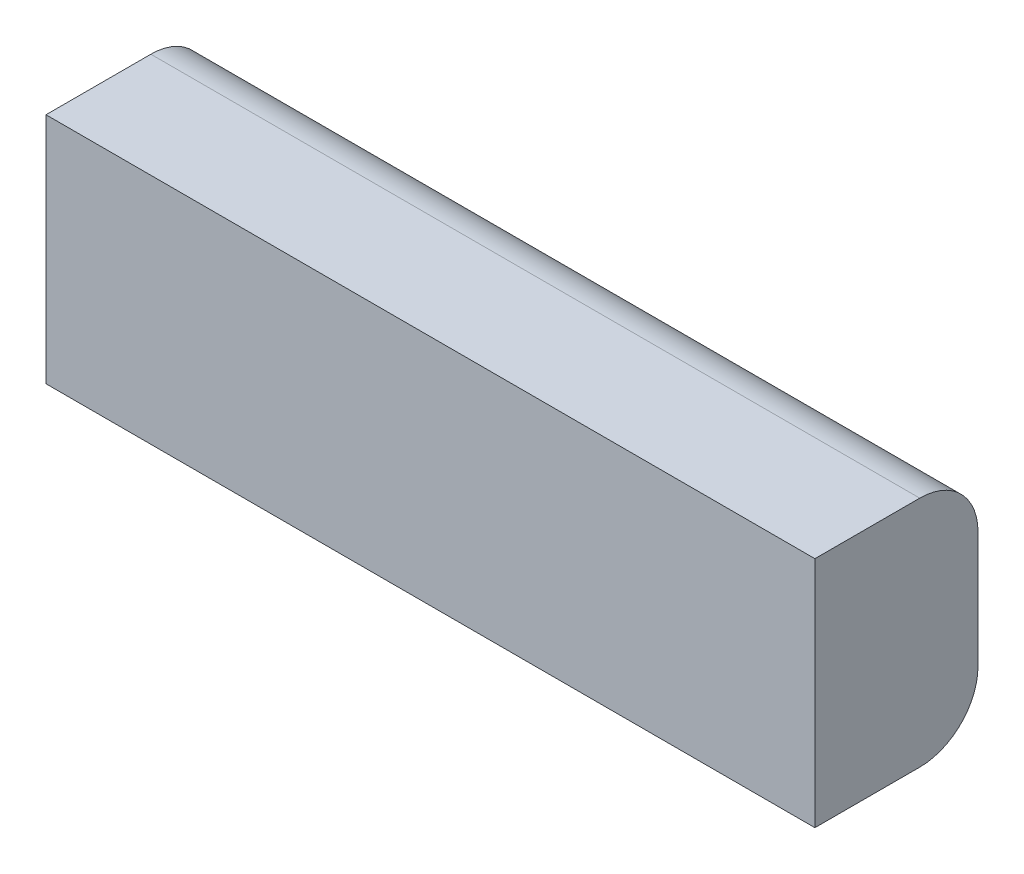
SolidWorks part; units mm, degrees
ref_plane "Front Plane" through (0, 0, 0) normal (0, 0, 1) x (1, 0, 0)
ref_plane "Top Plane" through (0, 0, 0) normal (0, 1, 0) x (1, 0, 0)
ref_plane "Right Plane" through (0, 0, 0) normal (1, 0, 0) x (0, 0, -1)
sketch "Sketch1" plane through (0, 0, 0) normal (1, 0, 0) x (0, 0, -1)
  line L1 (0, 0) -> (57.15, 0)
  line L2 (0, 0) -> (0, 127)
  line L3 (0, 127) -> (57.15, 127)
  line L4 (88.9, 31.75) -> (88.9, 95.25)
  arc A0 (57.15, 0) -> (88.9, 31.75) centre (57.15, 31.75) ccw
  arc A1 (57.15, 127) -> (88.9, 95.25) centre (57.15, 95.25) cw
  point P7 (88.9, 0)
  point P10 (88.9, 127)
  dimension "D3" = 31.75
  dimension "D1" = 88.9
  dimension "D2" = 127
extrude "Boss-Extrude1" add sketch "Sketch1" along normal blind 419.1
sketch "Sketch2" plane through (0, 0, -88.9) normal (0, 0, -1) x (-1, 0, 0)
  text T0 "4146" font "Century Gothic" height 50.8
extrude "Boss-Extrude2" add sketch "Sketch2" along normal blind 0.0254
